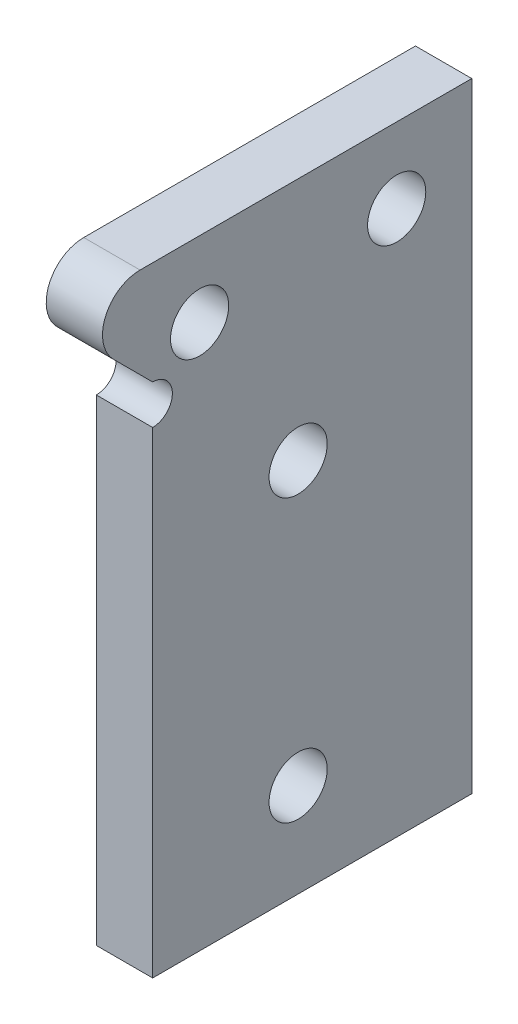
SolidWorks part; units mm, degrees
material "Thornel Mat VMA"
ref_plane "前视基准面" through (0, 0, 0) normal (0, 0, 1) x (1, 0, 0)
ref_plane "上视基准面" through (0, 0, 0) normal (0, 1, 0) x (1, 0, 0)
ref_plane "右视基准面" through (0, 0, 0) normal (1, 0, 0) x (0, 0, -1)
sketch "草图1" plane through (0, 0, 0) normal (1, 0, 0) x (0, 0, -1)
  line L0 (0, 0) -> (0, 27.5)
  line L1 (0, 27.5) -> (-5.5, 33)
  line L2 (-5.5, 33) -> (17, 33)
  line L3 (17, 33) -> (17, 0)
  line L4 (17, 0) -> (0, 0)
  line L5 (-7.3629, 29) -> (13, 29) construction
  line L6 (7.75, 21.55) -> (7.75, 8.5514) construction
  line L7 (0, 12.5) -> (10.8097, 12.5) construction
  circle A0 centre (2.5, 29) radius 1.55
  circle A1 centre (13, 29) radius 1.55
  circle A2 centre (0, 26.45) radius 1.05
  circle A3 centre (7.75, 20) radius 1.55
  circle A4 centre (7.75, 5) radius 1.55
  point P11 (5.75, 33)
  dimension "D3" = 3.1
  dimension "D9" = 2.1
  dimension "D1" = 27.5
  dimension "D2" = 33
  dimension "D4" = 2.5
  dimension "D5" = 10.5
  dimension "D6" = 4
  dimension "D7" = 4
  dimension "D8" = 45
  dimension "D10" = 12.5
  dimension "D11" = 15
extrude "凸台-拉伸1" add sketch "草图1" along normal blind 3 contours A2 L0 L4 L3 L2 L1 A4 A3 A1 A0
fillet "圆角1" radius 2 1 edges at (1.5, 33, 5.5)
